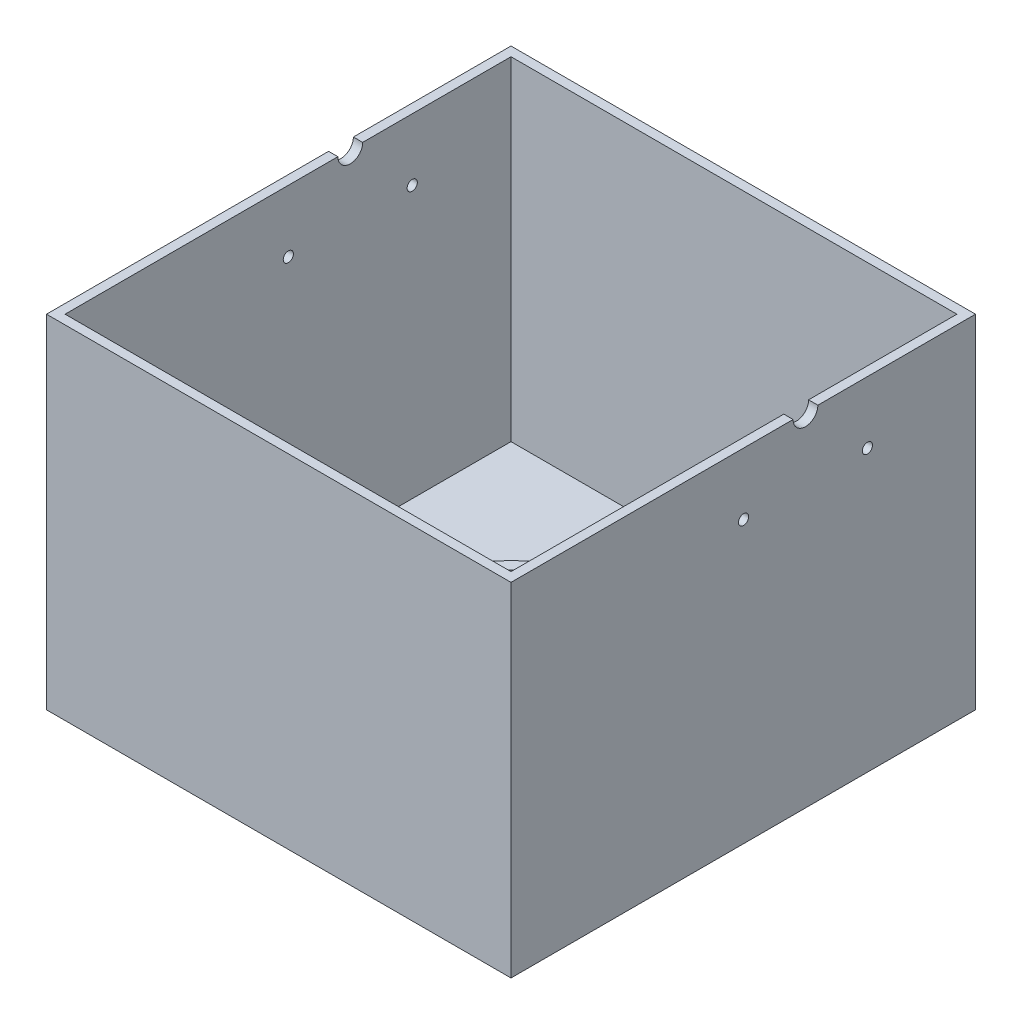
SolidWorks part; units mm, degrees
ref_plane "前视基准面" through (0, 0, 0) normal (0, 0, 1) x (1, 0, 0)
ref_plane "上视基准面" through (0, 0, 0) normal (0, 1, 0) x (1, 0, 0)
ref_plane "右视基准面" through (0, 0, 0) normal (1, 0, 0) x (0, 0, -1)
sketch "草图1" plane through (0, 0, 0) normal (0, 1, 0) x (1, 0, 0)
  line L1 (-75, 75) -> (75, 75)
  line L2 (-75, 75) -> (-75, -75)
  line L3 (-75, -75) -> (75, -75)
  line L4 (75, 75) -> (75, -75)
  line L5 (-75, 75) -> (75, -75) construction
  line L6 (-75, -75) -> (75, 75) construction
  point P0 (0, 0)
  dimension "D1" = 150
  dimension "D2" = 150
extrude "凸台-拉伸1" add sketch "草图1" along normal blind 3
sketch "草图2" plane through (0, 3, 0) normal (0, 1, 0) x (1, 0, 0)
  line L1 (75, -75) -> (-75, -75)
  line L2 (75, -75) -> (75, 75)
  line L3 (75, 75) -> (-75, 75)
  line L4 (-75, -75) -> (-75, 75)
  line L5 (75, -75) -> (-75, 75) construction
  line L6 (75, 75) -> (-75, -75) construction
  line L7 (72, -72) -> (-72, -72)
  line L8 (72, -72) -> (72, 72)
  line L9 (72, 72) -> (-72, 72)
  line L10 (-72, -72) -> (-72, 72)
  line L11 (72, -72) -> (-72, 72) construction
  line L12 (72, 72) -> (-72, -72) construction
  point P0 (0, 0)
  point P7 (0, 0)
  dimension "D1" = 144
extrude "凸台-拉伸2" add sketch "草图2" along normal blind 107.65
sketch "草图3" plane through (0, 0, 0) normal (0, -1, 0) x (1, 0, 0)
  circle A0 centre (0, 0) radius 27.5
  dimension "D1" = 55
extrude "切除-拉伸1" cut sketch "草图3" against normal blind 91
sketch "草图4" plane through (-75, 0, 0) normal (-1, 0, 0) x (0, 0, 1)
  line L0 (-75, 110.65) -> (75, 110.65) construction
  line L1 (-75, 110.65) -> (-75, 0) construction
  circle A0 centre (-20.1, 110.65) radius 4
  dimension "D1" = 8
  dimension "D2" = 54.9
extrude "切除-拉伸2" cut sketch "草图4" against normal through all
sketch "草图8" plane through (0, 3, 0) normal (0, 1, 0) x (1, 0, 0)
  circle A0 centre (0, 0) radius 31.25
  circle A1 centre (0, 0) radius 35
  dimension "D1" = 62.5
  dimension "D2" = 70
extrude "凸台-拉伸4" add sketch "草图8" along normal blind 14
sketch "草图9" plane through (-75, 0, 0) normal (-1, 0, 0) x (0, 0, 1)
  line L0 (-20.1, 106.65) -> (-20.1, 66.4211) construction
  line L2 (-75, 110.65) -> (-24.1, 110.65) construction
  arc A0 (-24.1, 110.65) -> (-16.1, 110.65) centre (-20.1, 110.65) ccw construction
  circle A1 centre (-40.1, 90.65) radius 1.65
  circle A2 centre (-0.1, 90.65) radius 1.65
  point P10 (0, 0)
  point P12 (4.0826, 108.8614)
  point P14 (0, 0)
  dimension "D1" = 3.3
  dimension "D2" = 3.3
  dimension "D3" = 40
  dimension "D4" = 20
extrude "切除-拉伸3" cut sketch "草图9" against normal through all
